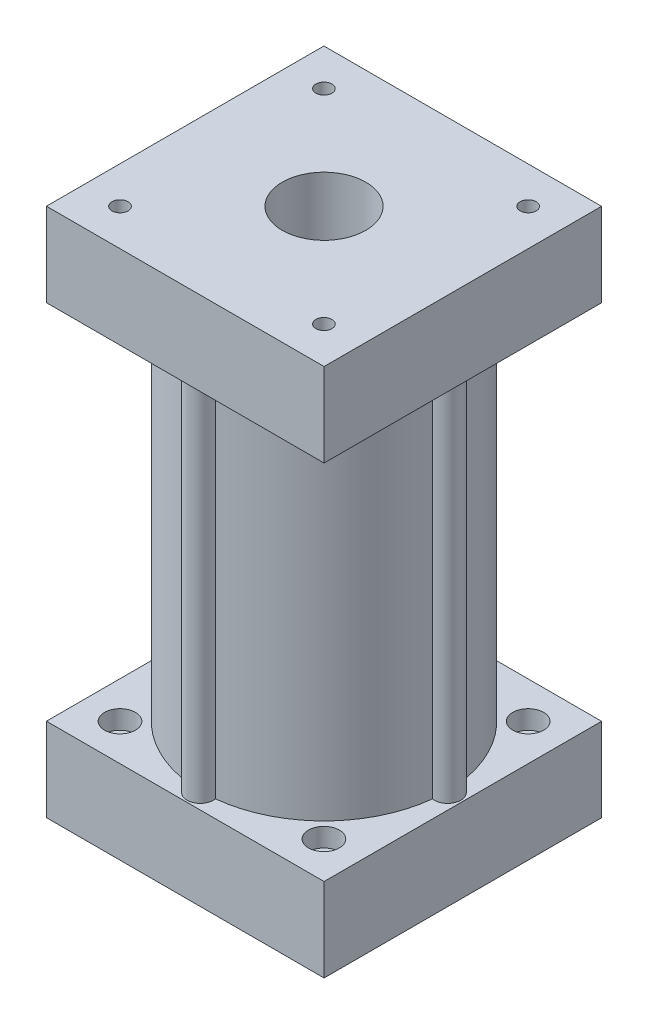
SolidWorks part; units mm, degrees
ref_plane "Front Plane" through (0, 0, 0) normal (0, 0, 1) x (1, 0, 0)
ref_plane "Top Plane" through (0, 0, 0) normal (0, 1, 0) x (1, 0, 0)
ref_plane "Right Plane" through (0, 0, 0) normal (1, 0, 0) x (0, 0, -1)
sketch "Sketch1" plane through (0, 0, 0) normal (0, 1, 0) x (1, 0, 0)
  line L0 (37.6058, -27.8428) -> (46.5873, -27.8428) construction
  line L7 (37.6058, -27.8428) -> (37.6058, -31.8855) construction
  line L9 (37.6058, -27.8428) -> (-4.5836, -27.8428)
  line L15 (-4.5836, 14.3212) -> (-13.6667, 14.3212) construction
  line L17 (-4.5836, 14.3212) -> (-4.5836, 21.2102) construction
  line L18 (37.6058, -27.8428) -> (37.6058, 14.3212)
  line L19 (37.6058, 14.3212) -> (-4.5836, 14.3212)
  line L20 (-4.5836, -27.8428) -> (-4.5836, 14.3212)
  circle A0 centre (16.5111, -6.7735) radius 16.51
  circle A1 centre (32.0305, 8.7459) radius 1.25
  circle A2 centre (1.0202, 8.7175) radius 1.25
  circle A3 centre (1.0202, -22.2644) radius 1.25
  circle A4 centre (32.0021, -22.2644) radius 1.25
  point P0 (0, 0)
  dimension "D1" = 33.02
extrude "Boss-Extrude1" add sketch "Sketch1" along normal blind 12.7
sketch "Sketch2" plane through (0, 12.7, 0) normal (0, 1, 0) x (1, 0, 0)
  line L0 (16.5111, 14.3212) -> (16.5111, 9.7365) construction
  line L1 (37.6058, 14.3212) -> (-4.5836, 14.3212) construction
  line L2 (0.0011, -6.7735) -> (-4.5836, -6.7608) construction
  line L3 (-4.5836, 14.3212) -> (-4.5836, -27.8428) construction
  line L4 (33.0211, -6.7735) -> (37.6058, -6.7608) construction
  line L5 (37.6058, -27.8428) -> (37.6058, 14.3212) construction
  line L6 (16.5111, -23.2835) -> (16.5111, -27.8428) construction
  line L7 (-4.5836, -27.8428) -> (37.6058, -27.8428) construction
  circle A0 centre (16.5111, -6.7735) radius 16.51 construction
  circle A1 centre (16.5111, 12.0289) radius 2
  circle A2 centre (-2.2912, -6.7671) radius 2
  circle A3 centre (35.3135, -6.7671) radius 2
  circle A4 centre (16.5111, -25.5631) radius 2
  dimension "D1" = 4
  dimension "D2" = 4
  dimension "D3" = 4
  dimension "D4" = 4
extrude "Boss-Extrude2" add sketch "Sketch2" along normal blind 55.0672
sketch "Sketch3" plane through (0, 67.7672, 0) normal (0, 1, 0) x (1, 0, 0)
  line L1 (-4.5836, 14.3212) -> (37.6058, 14.3212)
  line L2 (-4.5836, 14.3212) -> (-4.5836, -27.8428)
  line L3 (-4.5836, -27.8428) -> (37.6058, -27.8428)
  line L4 (37.6058, 14.3212) -> (37.6058, -27.8428)
  circle A0 centre (16.5111, -6.7608) radius 6.35
  dimension "D1" = 12.7
extrude "Boss-Extrude3" add sketch "Sketch3" along normal blind 12.7
sketch "Sketch4" plane through (0, 0, 0) normal (0, -1, 0) x (1, 0, 0)
  circle A0 centre (1.0202, 22.2644) radius 1.2192
  circle A1 centre (1.0202, -8.7175) radius 1.2192
  circle A2 centre (32.0305, -8.7459) radius 1.2192
  circle A3 centre (32.0021, 22.2644) radius 1.2192
  dimension "D1" = 2.4384
  dimension "D2" = 2.4384
  dimension "D3" = 2.4384
  dimension "D4" = 2.4384
extrude "Cut-Extrude1" cut sketch "Sketch4" against normal through all
sketch "Sketch5" plane through (0, 12.7, 0) normal (0, 1, 0) x (1, 0, 0)
  circle A0 centre (32.0021, -22.2644) radius 2.3495
  circle A1 centre (1.0202, -22.2644) radius 2.3495
  circle A2 centre (32.0305, 8.7459) radius 2.3495
  circle A3 centre (1.0202, 8.7175) radius 2.3495
  dimension "D1" = 4.699
  dimension "D2" = 4.699
  dimension "D3" = 4.699
  dimension "D4" = 4.699
extrude "Cut-Extrude2" cut sketch "Sketch5" against normal blind 2.8448
sketch "Sketch7" plane through (0, 67.7672, 0) normal (0, -1, 0) x (1, 0, 0)
  line L0 (1.0202, 22.2644) -> (1.0202, 27.8428) construction
  line L1 (-4.5836, 27.8428) -> (37.6058, 27.8428) construction
  line L2 (1.0202, 22.2644) -> (-4.5836, 22.2644) construction
  line L3 (-4.5836, -14.3212) -> (-4.5836, 27.8428) construction
  line L4 (1.0202, -8.7175) -> (-4.5836, -8.7175) construction
  line L5 (1.0202, -8.7175) -> (1.0202, -14.3212) construction
  line L6 (37.6058, -14.3212) -> (-4.5836, -14.3212) construction
  line L7 (32.0305, -8.7459) -> (32.0305, -14.3212) construction
  line L8 (32.0305, -8.7459) -> (37.6058, -8.7459) construction
  line L9 (37.6058, 27.8428) -> (37.6058, -14.3212) construction
  line L10 (32.0021, 22.2644) -> (32.0021, 27.8428) construction
  line L11 (32.0021, 22.2644) -> (37.6058, 22.2644) construction
  circle A0 centre (32.0305, -8.7459) radius 2.3368
  circle A1 centre (32.0021, 22.2644) radius 2.3368
  circle A2 centre (1.0202, -8.7175) radius 2.3368
  circle A3 centre (1.0202, 22.2644) radius 2.3368
  dimension "D1" = 4.6736
  dimension "D2" = 4.6736
  dimension "D3" = 4.6736
  dimension "D4" = 4.6736
  dimension "D5" = 5.5753
  dimension "D6" = 5.5753
extrude "Cut-Extrude3" cut sketch "Sketch7" against normal blind 2.8448
sketch "Sketch8" plane through (0, 67.7672, 0) normal (0, -1, 0) x (1, 0, 0)
  circle A0 centre (16.5111, 6.7608) radius 16.51
  circle A2 centre (16.5111, 6.7608) radius 18.565
  dimension "D1" = 33.02
extrude "Boss-Extrude5" add sketch "Sketch8" along normal blind 67.564
